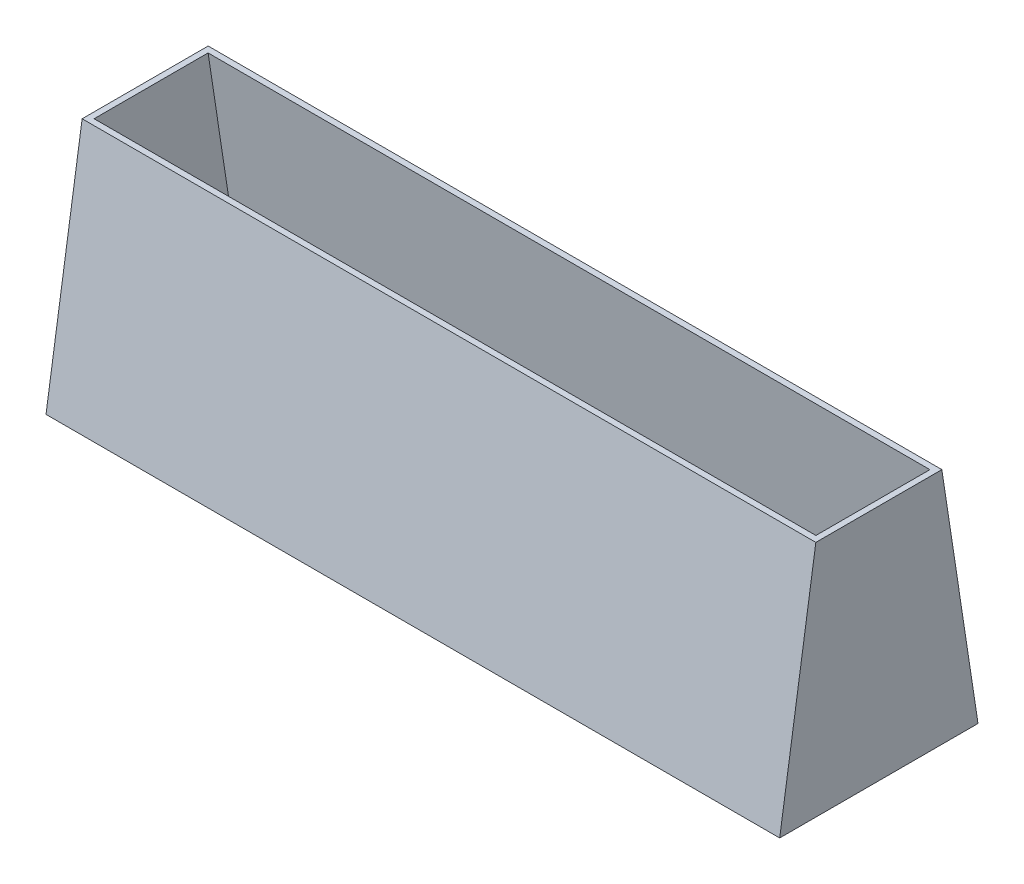
SolidWorks part; units mm, degrees
ref_plane "Front Plane" through (0, 0, 0) normal (0, 0, 1) x (1, 0, 0)
ref_plane "Top Plane" through (0, 0, 0) normal (0, 1, 0) x (1, 0, 0)
ref_plane "Right Plane" through (0, 0, 0) normal (1, 0, 0) x (0, 0, -1)
sketch "Sketch2" plane through (0, 0, 0) normal (1, 0, 0) x (0, 0, -1)
  line L19 (100, 0) -> (0, 0)
  line L20 (81.7778, 120) -> (100, 0)
  line L26 (18.2222, 120) -> (0, 0)
  line L27 (18.2222, 120) -> (81.7778, 120)
  dimension "D3" = 100
extrude "Boss-Extrude1" add sketch "Sketch2" along normal blind 370
shell "Shell1" thickness 3
sketch "Sketch3" plane through (0, 14.3925, -94.7801) normal (0, -0.1501, 0.9887) x (1, 0, 0)
  line L0 (367, -11.5231) -> (3, -11.5231) construction
  line L1 (280, 31.4769) -> (330, 31.4769)
  line L2 (280, 31.4769) -> (280, 28.4769)
  line L3 (280, 28.4769) -> (330, 28.4769)
  line L4 (330, 31.4769) -> (330, 28.4769)
  line L5 (370, 115.9042) -> (370, 0) construction
  dimension "D1" = 3
  dimension "D2" = 50
  dimension "D3" = 40
  dimension "D4" = 40
extrude "Boss-Extrude2" add sketch "Sketch3" along normal up to next
